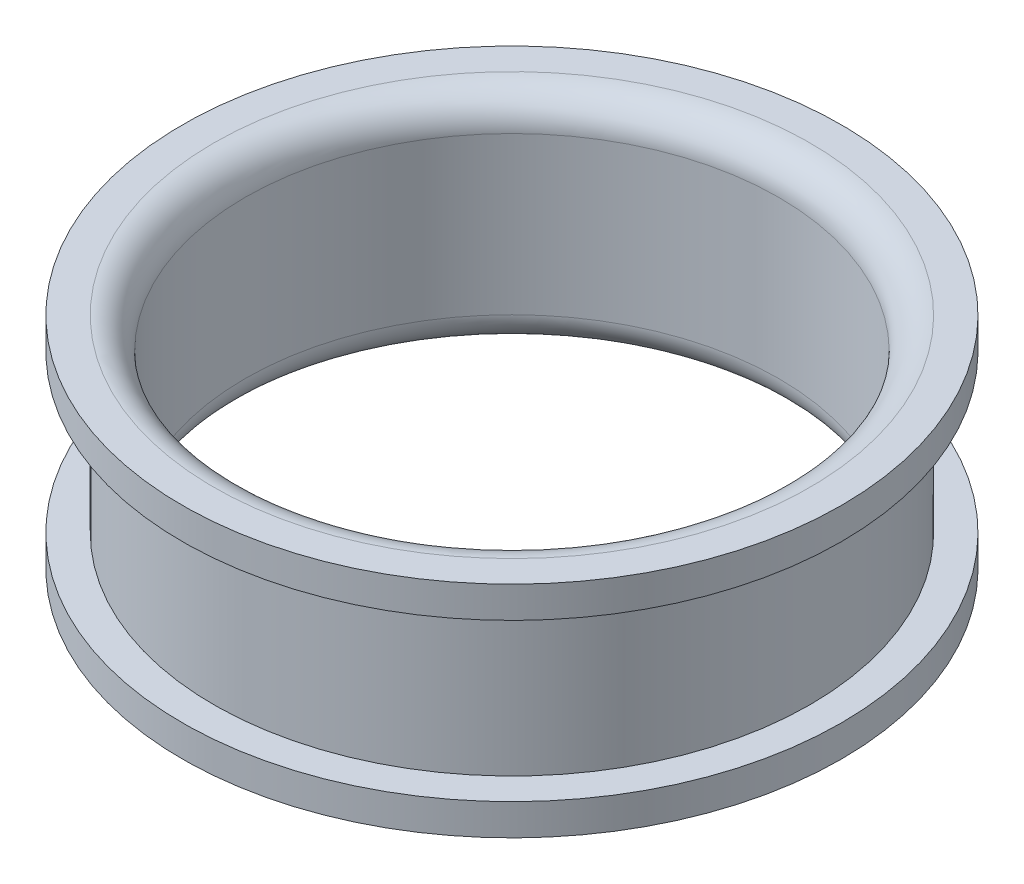
SolidWorks part; units mm, degrees
material "1.0060 (E335)"
ref_plane "Front Plane" through (0, 0, 0) normal (0, 0, 1) x (1, 0, 0)
ref_plane "Top Plane" through (0, 0, 0) normal (0, 1, 0) x (1, 0, 0)
ref_plane "Right Plane" through (0, 0, 0) normal (1, 0, 0) x (0, 0, -1)
sketch "Sketch1" plane through (0, 0, 0) normal (0, 0, 1) x (1, 0, 0)
  line L0 (0, -1019.4497) -> (0, 49953.0371) construction
  line L1 (52.5, 17.5) -> (42.5, 17.5)
  line L2 (42.5, 17.5) -> (42.5, -17.5)
  line L3 (42.5, -17.5) -> (52.5, -17.5)
  line L4 (52.5, -17.5) -> (52.5, -12.5)
  line L5 (52.5, -12.5) -> (47.5, -12.5)
  line L6 (47.5, -12.5) -> (47.5, 12.5)
  line L7 (47.5, 12.5) -> (52.5, 12.5)
  line L8 (52.5, 12.5) -> (52.5, 17.5)
  point P1 (42.5, 0)
  point P9 (47.5, 0)
  dimension "D1" = 5
  dimension "D2" = 85
  dimension "D3" = 35
  dimension "D4" = 25
  dimension "D5" = 105
revolve "Revolve1" add sketch "Sketch1" angle 360 about L0
fillet "Fillet1" radius 5 2 edges at (42.5, 17.5, 0) (42.5, -17.5, 0)
